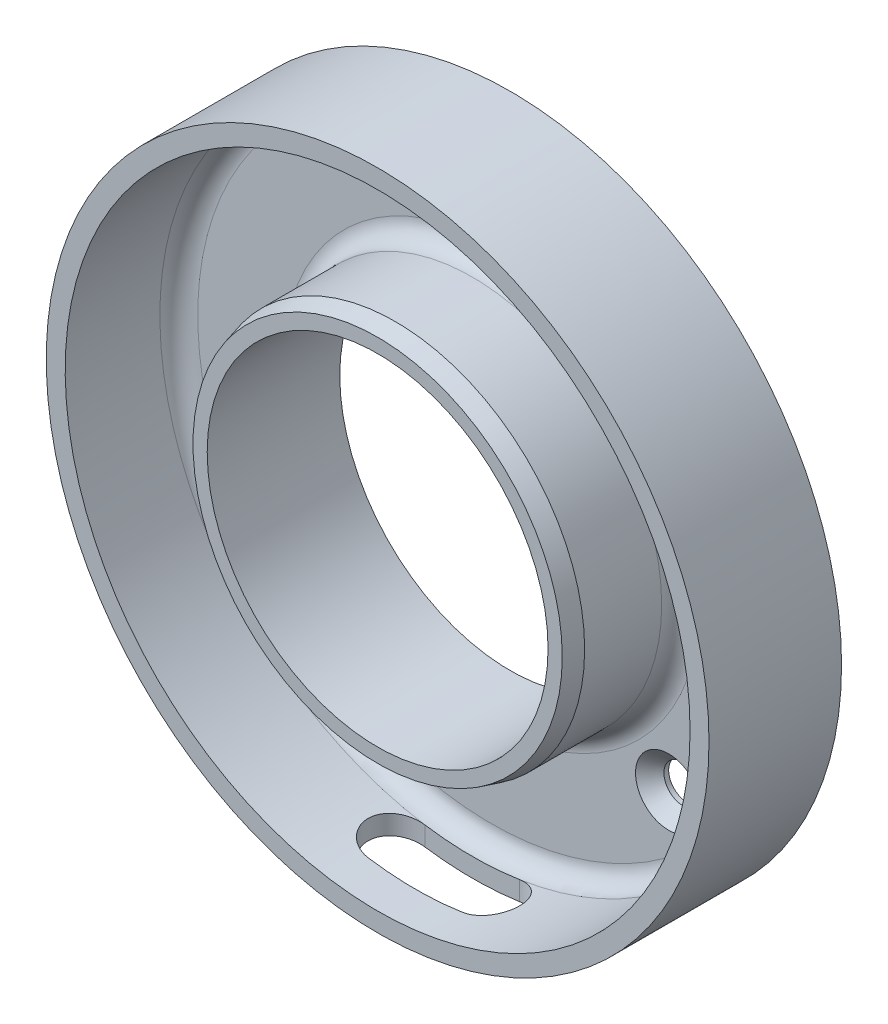
SolidWorks part; units mm, degrees
ref_plane "Alzado" through (0, 0, 0) normal (0, 0, 1) x (1, 0, 0)
ref_plane "Planta" through (0, 0, 0) normal (0, 1, 0) x (1, 0, 0)
ref_plane "Vista lateral" through (0, 0, 0) normal (1, 0, 0) x (0, 0, -1)
sketch "Croquis1" plane through (0, 0, 0) normal (0, 0, 1) x (1, 0, 0)
  circle A0 centre (0, 0) radius 35
  dimension "D1" = 70
extrude "Saliente-Extruir1" add sketch "Croquis1" along normal blind 14
sketch "Croquis2" plane through (0, 0, 14) normal (0, 0, 1) x (1, 0, 0)
  circle A0 centre (0, 0) radius 18
  dimension "D1" = 36
extrude "Cortar-Extruir1" cut sketch "Croquis2" against normal through all
shell "Vaciado1" thickness 2
fillet "Redondeo1" radius 2 2 edges at (20, 0, 2) (33, 0, 2)
sketch "Croquis3" plane through (0, 0, 0) normal (0, 1, 0) x (1, 0, 0)
  line L0 (-5, -7) -> (5, -7) construction
  line L1 (-5, -4) -> (5, -4)
  line L2 (-5, -10) -> (5, -10)
  line L3 (0, 0) -> (0, -14) construction
  line L4 (-35, -14) -> (35, -14) construction
  arc A0 (-5, -4) -> (-5, -10) centre (-5, -7) ccw
  arc A1 (5, -10) -> (5, -4) centre (5, -7) ccw
  point P2 (0, -7)
  dimension "D1" = 3
  dimension "D2" = 10
extrude "Cortar-Extruir2" cut sketch "Croquis3" against normal through all from offset 22 offset against normal yes
sketch "Croquis4" plane through (0, 0, 2) normal (0, 0, 1) x (1, 0, 0)
  line L0 (-8.1156, -27.8708) -> (-9.4991, -27.1121)
  line L1 (-9.4991, -27.1121) -> (-9.0591, -26.3096)
  line L2 (-9.0591, -26.3096) -> (-10.9845, -26.8712)
  line L3 (-10.9845, -26.8712) -> (-10.4229, -28.7966)
  line L4 (-10.4229, -28.7966) -> (-10.0218, -28.0651)
  line L5 (-10.0218, -28.0651) -> (-8.6383, -28.8238)
  line L6 (-8.6383, -28.8238) -> (-8.1156, -27.8708)
  line L7 (0, 0) -> (0, -35) construction
  line L8 (0, 0) -> (24.7487, -24.7487) construction
  line L9 (0, 0) -> (-24.7487, -24.7487) construction
  circle A0 centre (0, 0) radius 35 construction
  circle A1 centre (-18.7383, -18.7383) radius 2
  circle A2 centre (18.7383, -18.7383) radius 2
  dimension "D3" = 4
  dimension "D4" = 4
  dimension "D5" = 26.5
  dimension "D6" = 26.5
  dimension "D1" = 45
  dimension "D2" = 45
extrude "Cortar-Extruir3" cut sketch "Croquis4" against normal through all
chamfer "Chaflán1" distance 1.5 angle 45 2 edges at (20.7383, -18.7383, 2) (-16.7383, -18.7383, 2)
chamfer "Chaflán2" distance 0.5 angle 75 1 edges at (20, 0, 14)
